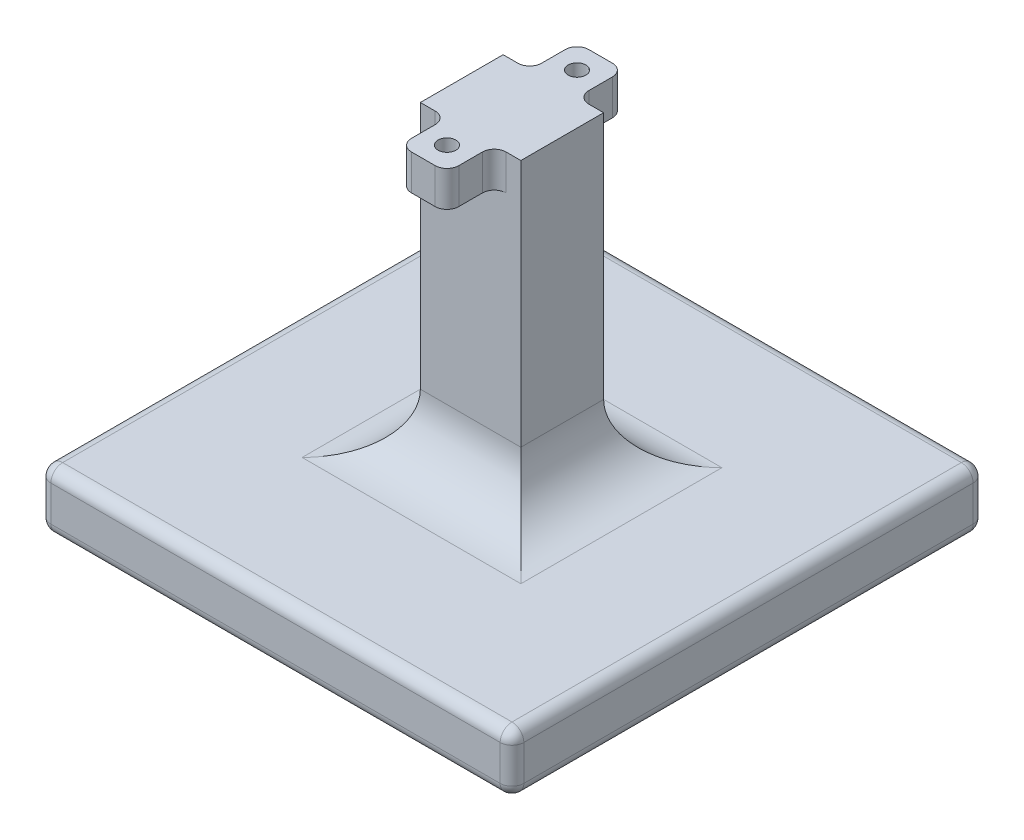
SolidWorks part; units mm, degrees
ref_plane "Спереди" through (0, 0, 0) normal (0, 0, 1) x (1, 0, 0)
ref_plane "Сверху" through (0, 0, 0) normal (0, 1, 0) x (1, 0, 0)
ref_plane "Справа" through (0, 0, 0) normal (1, 0, 0) x (0, 0, -1)
sketch "Sketch1" plane through (0, 0, 0) normal (0, 1, 0) x (1, 0, 0)
  line L1 (0, 0) -> (17, 0)
  line L2 (0, 0) -> (0, -14)
  line L3 (0, -14) -> (17, -14)
  line L4 (17, 0) -> (17, -14)
  dimension "D1" = 14
  dimension "D2" = 17
extrude "Boss-Extrude1" add sketch "Sketch1" along normal blind 52
sketch "Sketch2" plane through (0, 0, 0) normal (0, -1, 0) x (1, 0, 0)
  line L0 (17, 0) -> (0, 0) construction
  line L1 (-31.5, 47) -> (48.5, 47)
  line L2 (-31.5, 47) -> (-31.5, -33)
  line L3 (-31.5, -33) -> (48.5, -33)
  line L4 (48.5, 47) -> (48.5, -33)
  line L5 (0, 0) -> (0, 14) construction
  dimension "D1" = 80
  dimension "D2" = 80
  dimension "D3" = 33
  dimension "D4" = 31.5
extrude "Boss-Extrude2" add sketch "Sketch2" along normal blind 10
sketch "Sketch3" plane through (0, 52, 0) normal (0, 1, 0) x (1, 0, 0)
  line L0 (8.5, 0) -> (8.5, -14) construction
  line L1 (17, 0) -> (0, 0) construction
  line L2 (0, -14) -> (17, -14) construction
  line L3 (0, -7) -> (17, -7) construction
  line L4 (4.5, 0) -> (12.5, 0)
  line L5 (4.5, 0) -> (4.5, 8)
  line L6 (4.5, 8) -> (12.5, 8)
  line L7 (12.5, 0) -> (12.5, 8)
  line L8 (0, 0) -> (0, -14) construction
  line L9 (17, -14) -> (17, 0) construction
  line L10 (4.5, 8) -> (12.5, 0) construction
  line L11 (4.5, -14) -> (12.5, -14)
  line L12 (12.5, -14) -> (12.5, -22)
  line L13 (4.5, -14) -> (4.5, -22)
  line L14 (4.5, -22) -> (12.5, -22)
  circle A0 centre (8.5, 4) radius 1.5
  circle A1 centre (8.5, -18) radius 1.5
  dimension "D4" = 3
  dimension "D1" = 8
  dimension "D2" = 8
  dimension "D3" = 4
extrude "Boss-Extrude3" add sketch "Sketch3" against normal blind 6
fillet "Fillet1" radius 2 8 edges at (4.5, 49, 0) (4.5, 49, -8) (12.5, 49, -8) (12.5, 49, 0) (12.5, 49, 14) (12.5, 49, 22) (4.5, 49, 22) (4.5, 49, 14)
fillet "Fillet2" radius 10 4 edges at (8.5, 0, 0) (17, 0, 7) (8.5, 0, 14) (0, 0, 7)
sketch "Sketch4" plane through (0, -10, 0) normal (0, -1, 0) x (1, 0, 0)
  line L0 (8.5, 47) -> (8.5, -33) construction
  line L1 (48.5, 47) -> (-31.5, 47) construction
  line L2 (-31.5, -33) -> (48.5, -33) construction
  line L3 (-31.5, 7) -> (48.5, 7) construction
  line L4 (-31.5, 47) -> (-31.5, -33) construction
  line L5 (48.5, -33) -> (48.5, 47) construction
  circle A0 centre (-25.5, 41) radius 3
  circle A1 centre (-25.5, -27) radius 3
  circle A2 centre (42.5, -27) radius 3
  circle A3 centre (42.5, 41) radius 3
  dimension "D1" = 6
  dimension "D2" = 6
  dimension "D3" = 6
extrude "Boss-Extrude4" add sketch "Sketch4" along normal blind 2
fillet "Fillet4" radius 1 4 edges at (-25.5, -12, 38) (42.5, -12, 44) (42.5, -12, -30) (-25.5, -12, -24)
fillet "Fillet3" radius 2 12 edges at (-31.5, -10, 7) (-31.5, -5, -33) (8.5, -10, -33) (48.5, -5, -33) (48.5, -10, 7) (8.5, -10, 47) (48.5, -5, 47) (-31.5, -5, 47) (8.5, 0, 47) (-31.5, 0, 7) (8.5, 0, -33) (48.5, 0, 7)
